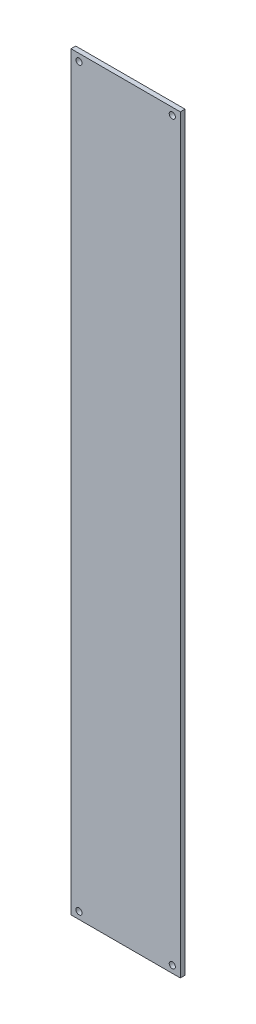
SolidWorks part; units mm, degrees
ref_plane "Piano frontale" through (0, 0, 0) normal (0, 0, 1) x (1, 0, 0)
ref_plane "Piano superiore" through (0, 0, 0) normal (0, 1, 0) x (1, 0, 0)
ref_plane "Piano destro" through (0, 0, 0) normal (1, 0, 0) x (0, 0, -1)
ref_plane "Piano1" through (0, 0, 5) normal (0, 0, 1) x (1, 0, 0)
sketch "Schizzo1" plane through (0, 0, 5) normal (0, 0, 1) x (1, 0, 0)
  line L4 (-2.5, -197.5) -> (-2.5, 598.5)
  line L5 (-2.5, 598.5) -> (-118.5, 598.5)
  line L6 (-118.5, 598.5) -> (-118.5, -197.5)
  line L7 (-118.5, -197.5) -> (-2.5, -197.5)
  circle A0 centre (-110, -190) radius 3.25
  circle A1 centre (-110, 591) radius 3.25
  circle A2 centre (-11, 591) radius 3.25
  circle A3 centre (-11, -190) radius 3.25
  dimension "D3" = 7.5
  dimension "D7" = 7.5
  dimension "D1" = 116
  dimension "D2" = 8.5
  dimension "D4" = 8.5
  dimension "D5" = 796
  dimension "D6" = 7.5
extrude "Estrusione-Estrusione1" add sketch "Schizzo1" against normal blind 5
